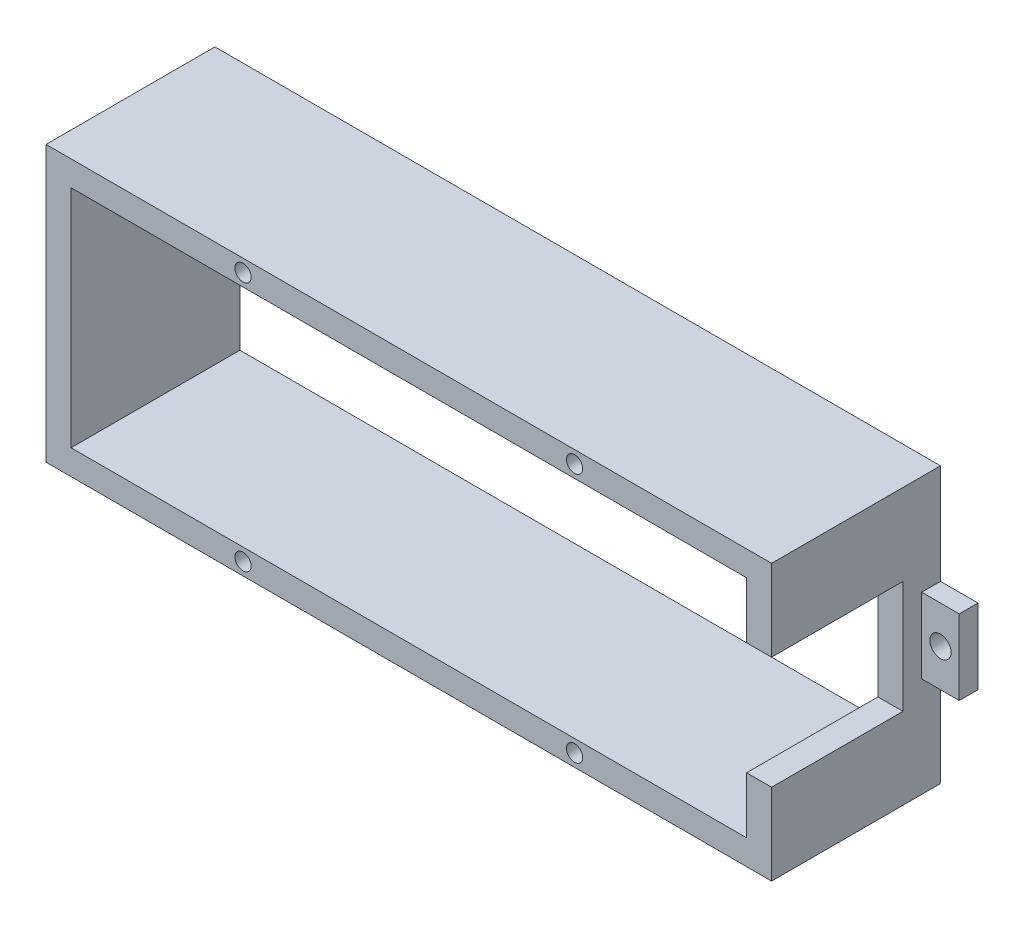
SolidWorks part; units mm, degrees
ref_plane "Front Plane" through (0, 0, 0) normal (0, 0, 1) x (1, 0, 0)
ref_plane "Top Plane" through (0, 0, 0) normal (0, 1, 0) x (1, 0, 0)
ref_plane "Right Plane" through (0, 0, 0) normal (1, 0, 0) x (0, 0, -1)
ref_plane "P_Front_60" through (0, 0, 60) normal (0, 0, 1) x (1, 0, 0)
sketch "Sketch1" plane through (0, 0, 60) normal (0, 0, 1) x (1, 0, 0)
  line L0 (-58, 20) -> (58, 20)
  line L1 (58, 20) -> (58, 64)
  line L2 (58, 64) -> (-58, 64)
  line L3 (-58, 64) -> (-58, 20)
  line L4 (-54, 24) -> (54, 24)
  line L5 (54, 24) -> (54, 60)
  line L6 (54, 60) -> (-54, 60)
  line L7 (-54, 60) -> (-54, 24)
extrude "Walls" add sketch "Sketch1" along normal blind 27
sketch "Sketch2" plane through (0, 0, 60) normal (0, 0, 1) x (1, 0, 0)
  line L0 (58, 36) -> (64, 36)
  line L1 (64, 36) -> (64, 48)
  line L2 (64, 48) -> (58, 48)
  line L3 (58, 48) -> (58, 36)
  line L4 (-64, 36) -> (-58, 36)
  line L5 (-58, 36) -> (-58, 48)
  line L6 (-58, 48) -> (-64, 48)
  line L7 (-64, 48) -> (-64, 36)
extrude "Floor_tabs" add sketch "Sketch2" along normal blind 3
ref_plane "P_Front_59" through (0, 0, 59) normal (0, 0, 1) x (1, 0, 0)
sketch "Sketch3" plane through (0, 0, 59) normal (0, 0, 1) x (1, 0, 0)
  circle A0 centre (61, 42) radius 1.7
  circle A1 centre (-61, 42) radius 1.7
extrude "Tab_holes" cut sketch "Sketch3" along normal blind 5
ref_plane "P_Front_79" through (0, 0, 79) normal (0, 0, 1) x (1, 0, 0)
sketch "Sketch4" plane through (0, 0, 79) normal (0, 0, 1) x (1, 0, 0)
  line L0 (21.5, 60) -> (31.5, 60)
  line L1 (31.5, 60) -> (31.5, 64)
  line L2 (31.5, 64) -> (21.5, 64)
  line L3 (21.5, 64) -> (21.5, 60)
  line L4 (-31.5, 60) -> (-21.5, 60)
  line L5 (-21.5, 60) -> (-21.5, 64)
  line L6 (-21.5, 64) -> (-31.5, 64)
  line L7 (-31.5, 64) -> (-31.5, 60)
  line L8 (21.5, 20) -> (31.5, 20)
  line L9 (31.5, 20) -> (31.5, 24)
  line L10 (31.5, 24) -> (21.5, 24)
  line L11 (21.5, 24) -> (21.5, 20)
  line L12 (-31.5, 20) -> (-21.5, 20)
  line L13 (-21.5, 20) -> (-21.5, 24)
  line L14 (-21.5, 24) -> (-31.5, 24)
  line L15 (-31.5, 24) -> (-31.5, 20)
extrude "Bar_bosses" add sketch "Sketch4" along normal blind 8
sketch "Sketch5" plane through (0, 0, 79) normal (0, 0, 1) x (1, 0, 0)
  circle A0 centre (26.5, 62) radius 1.3
  circle A1 centre (26.5, 22) radius 1.3
  circle A2 centre (-26.5, 62) radius 1.3
  circle A3 centre (-26.5, 22) radius 1.3
extrude "Bar_pilots" cut sketch "Sketch5" along normal blind 9
ref_plane "P_Right_53" through (53, 0, 0) normal (1, 0, 0) x (0, 0, -1)
sketch "Sketch6" plane through (53, 0, 0) normal (1, 0, 0) x (0, 0, -1)
  line L0 (-88, 33) -> (-66, 33)
  line L1 (-66, 33) -> (-66, 51)
  line L2 (-66, 51) -> (-88, 51)
  line L3 (-88, 51) -> (-88, 33)
extrude "Lead_exit" cut sketch "Sketch6" along normal blind 6
